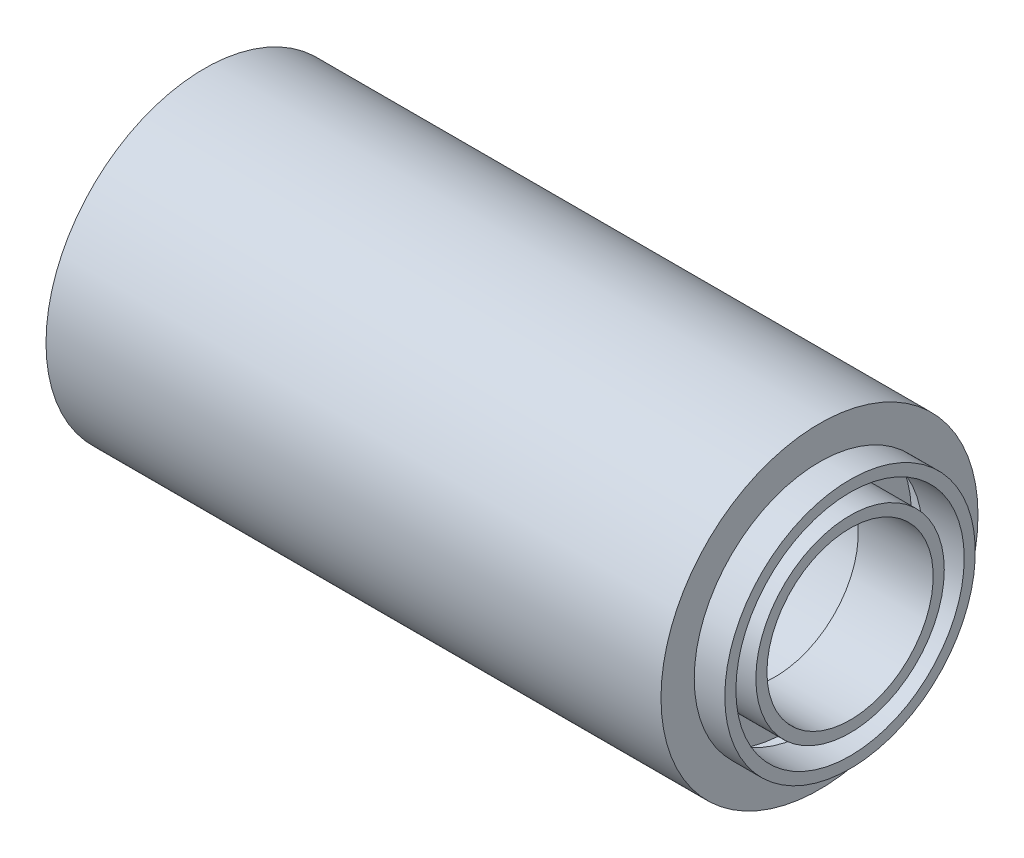
SolidWorks part; units mm, degrees
ref_plane "Front Plane" through (0, 0, 0) normal (0, 0, 1) x (1, 0, 0)
ref_plane "Top Plane" through (0, 0, 0) normal (0, 1, 0) x (1, 0, 0)
ref_plane "Right Plane" through (0, 0, 0) normal (1, 0, 0) x (0, 0, -1)
sketch "Sketch1" plane through (0, 0, 0) normal (0, 0, 1) x (1, 0, 0)
  line L5 (0, 0) -> (152.3613, 0)
  line L8 (0, 28.702) -> (0, 21.59)
  line L21 (0, 28.702) -> (125.6847, 28.702)
  line L22 (-5.08, 33.782) -> (130.7647, 33.782)
  line L23 (-5.08, 33.782) -> (-5.08, 26.162)
  line L35 (-5.08, 26.162) -> (-12.0906, 26.162)
  line L36 (-12.0906, 28.702) -> (-12.0906, 26.162)
  line L37 (-12.0906, 28.702) -> (-7.62, 28.702)
  line L38 (-7.62, 28.702) -> (-7.62, 36.322)
  line L39 (-7.62, 36.322) -> (133.3047, 36.322)
  line L40 (130.7647, 33.782) -> (130.7647, 26.162)
  line L41 (130.7647, 26.162) -> (140.3094, 26.162)
  line L42 (140.3094, 26.162) -> (140.3094, 28.702)
  line L43 (140.3094, 28.702) -> (133.3047, 28.702)
  line L44 (133.3047, 28.702) -> (133.3047, 36.322)
  line L45 (0, 21.59) -> (-12.0906, 21.59)
  line L46 (-12.0906, 21.59) -> (-12.0906, 19.05)
  line L47 (-12.0906, 19.05) -> (2.54, 19.05)
  line L48 (2.54, 19.05) -> (2.54, 26.162)
  line L49 (2.54, 26.162) -> (123.1447, 26.162)
  line L50 (123.1447, 26.162) -> (123.1447, 19.05)
  line L51 (123.1447, 19.05) -> (140.3094, 19.05)
  line L52 (140.3094, 19.05) -> (140.3094, 21.59)
  line L53 (140.3094, 21.59) -> (125.6847, 21.59)
  line L54 (125.6847, 21.59) -> (125.6847, 28.702)
  point P18 (130.7647, 29.972)
  dimension "D1" = 152.4
  dimension "D2" = 152.4
  dimension "D3" = 5.08
  dimension "D4" = 5.08
  dimension "D5" = 5.08
  dimension "D6" = 2.54
  dimension "D7" = 2.54
  dimension "D8" = 2.54
  dimension "D9" = 7.62
  dimension "D10" = 2.54
  dimension "D11" = 7.62
  dimension "D12" = 2.54
  dimension "D13" = 2.54
  dimension "D14" = 2.54
  dimension "D15" = 2.54
  dimension "D16" = 2.54
  dimension "D17" = 4.572
  dimension "D18" = 4.572
  dimension "D19" = 2.54
  dimension "D20" = 26.162
  dimension "D21" = 0
revolve "Revolve1" add sketch "Sketch1" angle 360 about L5
